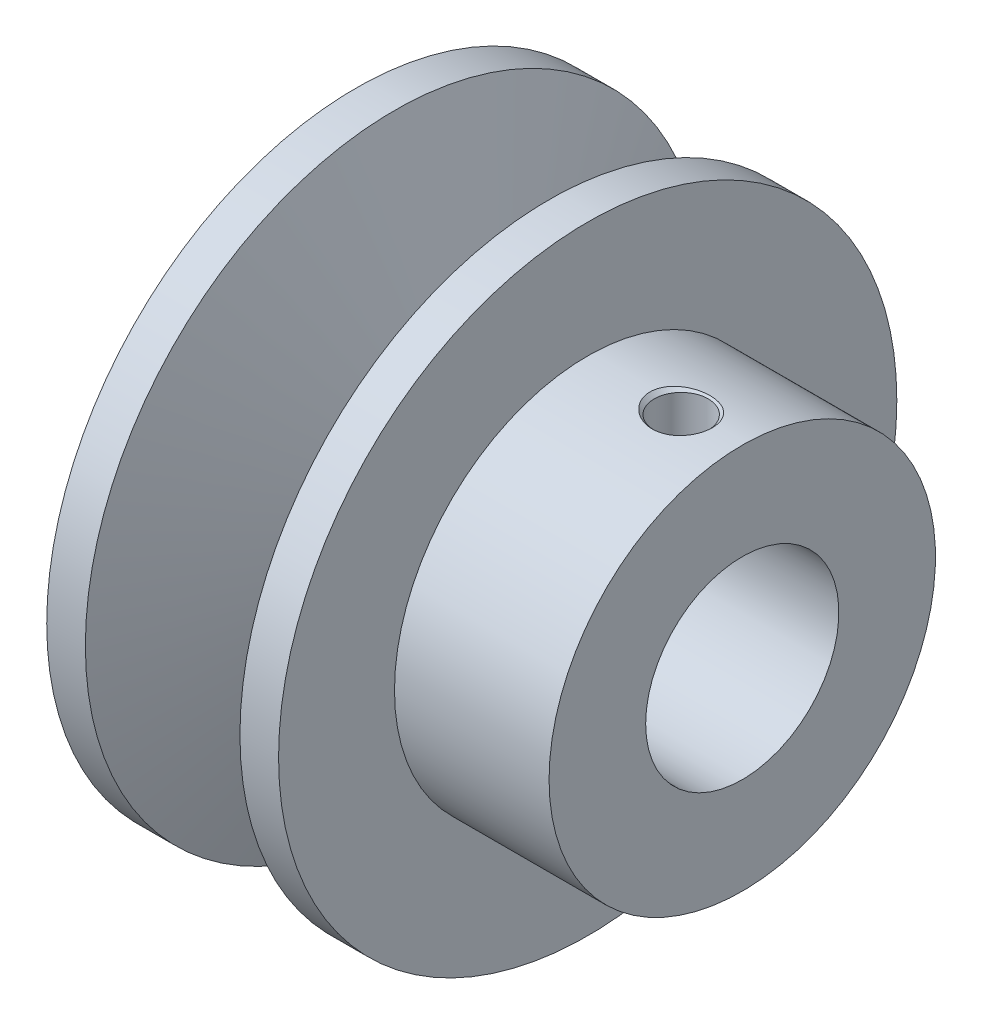
SolidWorks part; units mm, degrees
ref_plane "Front Plane" through (0, 0, 0) normal (0, 0, 1) x (1, 0, 0)
ref_plane "Top Plane" through (0, 0, 0) normal (0, 1, 0) x (1, 0, 0)
ref_plane "Right Plane" through (0, 0, 0) normal (1, 0, 0) x (0, 0, -1)
sketch "Sketch1" plane through (0, 0, 0) normal (0, 0, 1) x (1, 0, 0)
  line L1 (0, 0) -> (5, 0)
  line L2 (5, 0) -> (5, 12.5)
  line L3 (5, 12.5) -> (0, 20)
  line L4 (5, 12.5) -> (50, 12.5)
  line L5 (50, 12.5) -> (50, 25)
  line L6 (30, 40) -> (30, 25)
  line L7 (15, 20) -> (15, 43.8472) construction
  line L8 (17.7206, 20) -> (25, 40)
  line L9 (25, 40) -> (30, 40)
  line L10 (17.7206, 20) -> (12.2794, 20)
  line L11 (12.2794, 20) -> (5, 40)
  line L12 (5, 40) -> (0, 40)
  line L14 (0, 0) -> (50, 0) construction
  line L15 (30, 25) -> (50, 25)
  line L16 (0, 20) -> (0, 40)
  dimension "D1" = 20
  dimension "D2" = 12.5
  dimension "D3" = 15
  dimension "D4" = 40
  dimension "D5" = 5
  dimension "D6" = 12.2794
revolve "Revolve2" add sketch "Sketch1" angle 360 about L14
hole_wizard "M8x1.0 Tapped Hole2" positions "3DSketch3" profile "Sketch7" tap size "M8x1.0" standard "ISO"
sketch3d "3DSketch3"
  point P0 (42.0953, 25, 0)
sketch "Sketch7" plane through (42.0953, 25, 0) normal (1, 0, 0) x (0, 0, 1)
  line L0 (0, 0) -> (0, 21.103)
  line L1 (0, 21.103) -> (3.5, 19)
  line L2 (3.5, 19) -> (3.5, 0.525)
  line L3 (3.5, 0.525) -> (4.025, 0)
  line L5 (4.025, 0) -> (0, 0)
  line L6 (-3.5, 0.525) -> (-4.025, 0) construction
  line L10 (0, 21.103) -> (-3.5, 19) construction
  line L11 (0, -6.35) -> (0, 107.95) construction
  dimension "Tap Drill Dia." = 7
  dimension "Tap Drill Depth" = 19
  dimension "Near C'Sink Dia." = 8.05
  dimension "Near C'Sink Angle" = 90
  dimension "Drill Angle" = 118
